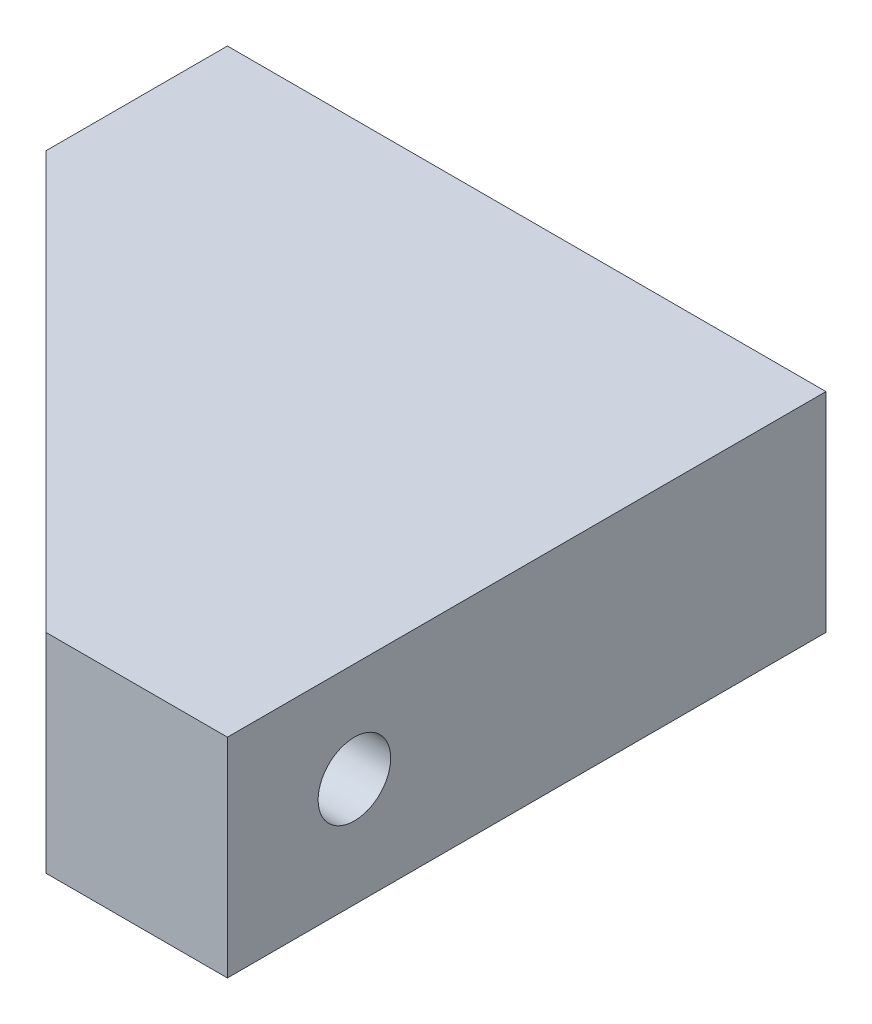
SolidWorks part; units mm, degrees
ref_plane "Front Plane" through (0, 0, 0) normal (0, 0, 1) x (1, 0, 0)
ref_plane "Top Plane" through (0, 0, 0) normal (0, 1, 0) x (1, 0, 0)
ref_plane "Right Plane" through (0, 0, 0) normal (1, 0, 0) x (0, 0, -1)
sketch "Sketch1" plane through (0, 0, 0) normal (0, 0, 1) x (1, 0, 0)
  line L1 (-31.9394, 9.2083) -> (1.0606, 9.2083)
  line L2 (-31.9394, 9.2083) -> (-31.9394, -13.7917)
  line L3 (-31.9394, -13.7917) -> (1.0606, -13.7917)
  line L4 (1.0606, 9.2083) -> (1.0606, -13.7917)
  dimension "D1" = 23
  dimension "D2" = 33
extrude "Boss-Extrude1" add sketch "Sketch1" along normal blind 10
sketch "Sketch2" plane through (0, 0, 10) normal (0, 0, 1) x (1, 0, 0)
  line L0 (-31.9394, -13.7917) -> (1.0606, -13.7917) construction
  line L1 (1.0606, 9.2083) -> (-8.9394, 9.2083)
  line L2 (1.0606, 9.2083) -> (1.0606, -13.7917)
  line L3 (1.0606, -13.7917) -> (-8.9394, -13.7917)
  line L4 (-8.9394, 9.2083) -> (-8.9394, -13.7917)
  dimension "D1" = 10
extrude "Boss-Extrude2" add sketch "Sketch2" along normal blind 23
sketch "Sketch3" plane through (0, 0, 10) normal (0, 0, 1) x (1, 0, 0)
  line L0 (-31.9394, -13.7917) -> (-8.9394, -13.7917) construction
  line L1 (-8.9394, 9.2083) -> (-31.9394, 9.2083) construction
  line L2 (-31.9394, 9.2083) -> (-31.9394, -13.7917) construction
  circle A0 centre (-24.9394, 3.2083) radius 2
  circle A1 centre (-24.9394, -7.7917) radius 2
  dimension "D1" = 4
  dimension "D2" = 4
  dimension "D3" = 6
  dimension "D4" = 6
  dimension "D5" = 7
  dimension "D6" = 7
extrude "Cut-Extrude1" cut sketch "Sketch3" against normal blind 33
sketch "Sketch4" plane through (-8.9394, 0, 0) normal (-1, 0, 0) x (0, 0, 1)
  line L0 (33, 9.2083) -> (10, 9.2083) construction
  line L1 (33, -13.7917) -> (10, -13.7917) construction
  line L2 (33, 9.2083) -> (33, -13.7917) construction
  circle A0 centre (26, 3.2083) radius 2
  circle A1 centre (26, -7.7917) radius 2
  dimension "D1" = 4
  dimension "D2" = 4
  dimension "D3" = 6
  dimension "D4" = 6
  dimension "D5" = 7
  dimension "D6" = 7
extrude "Cut-Extrude2" cut sketch "Sketch4" against normal blind 33
sketch "Sketch5" plane through (0, -13.7917, 0) normal (0, -1, 0) x (-1, 0, 0)
  line L0 (8.9394, -10) -> (8.9394, -33)
  line L1 (8.9394, -33) -> (31.9394, -10)
  line L2 (31.9394, -10) -> (8.9394, -10)
extrude "Boss-Extrude3" add sketch "Sketch5" against normal up to vertex (23 mm away)
sketch "Sketch6" plane through (-8.9394, 0, 0) normal (1, 0, 0) x (0, 0, -1)
  circle A0 centre (-26, -7.7917) radius 3.5
  circle A1 centre (-26, 3.2083) radius 3.5
  dimension "D1" = 7
  dimension "D2" = 7
extrude "Cut-Extrude3" cut sketch "Sketch6" against normal blind 33
sketch "Sketch7" plane through (0, 0, 10) normal (0, 0, -1) x (-1, 0, 0)
  circle A0 centre (24.9394, -7.7917) radius 3.5
  circle A1 centre (24.9394, 3.2083) radius 3.5
  dimension "D1" = 7
  dimension "D2" = 7
extrude "Cut-Extrude4" cut sketch "Sketch7" against normal blind 33
sketch "Sketch8" plane through (-31.9394, 0, 0) normal (-1, 0, 0) x (0, 0, 1)
  line L0 (33, 9.2083) -> (33, -13.7917) construction
  line L1 (0, 9.2083) -> (33, 9.2083)
  line L2 (0, 9.2083) -> (0, -2.2917)
  line L3 (0, -2.2917) -> (33, -2.2917)
  line L4 (33, 9.2083) -> (33, -2.2917)
extrude "Cut-Extrude5" cut sketch "Sketch8" against normal blind 53
